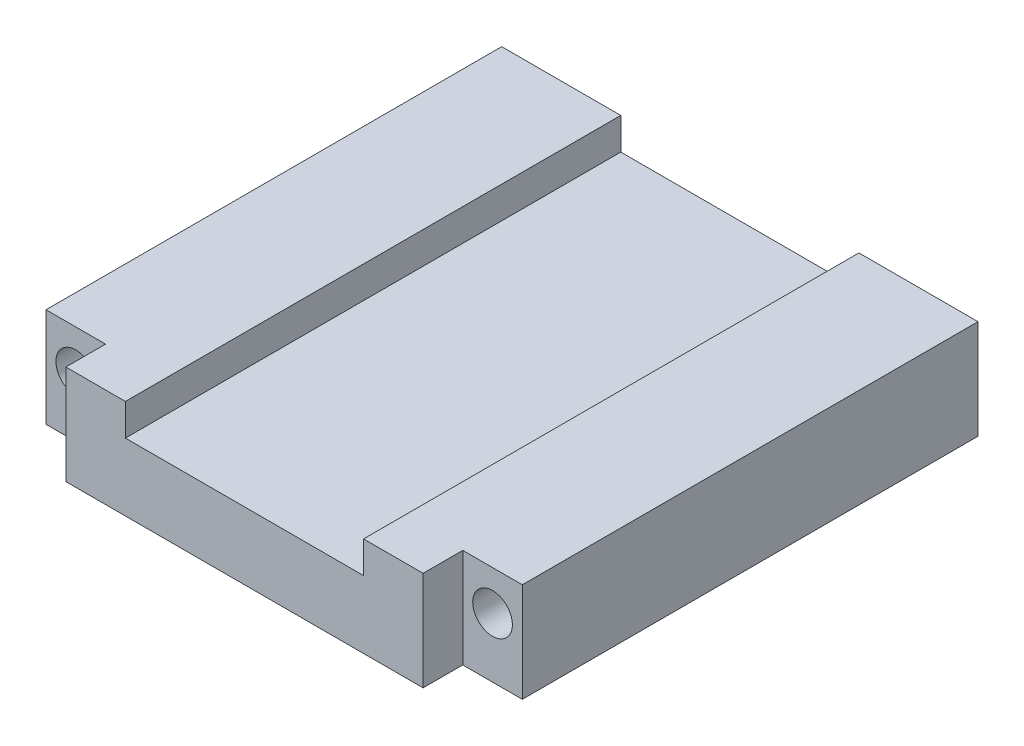
SolidWorks part; units mm, degrees
material "6063-O"
ref_plane "Front" through (0, 0, 0) normal (0, 0, 1) x (1, 0, 0)
ref_plane "Top" through (0, 0, 0) normal (0, 1, 0) x (1, 0, 0)
ref_plane "Right" through (0, 0, 0) normal (1, 0, 0) x (0, 0, -1)
sketch "Sketch1" plane through (0, 0, 0) normal (0, 0, 1) x (1, 0, 0)
  line L1 (19.05, -3.9687) -> (-19.05, -3.9688)
  line L2 (19.05, -3.9687) -> (19.05, 3.9688)
  line L3 (19.05, 3.9688) -> (-19.05, 3.9687)
  line L4 (-19.05, -3.9688) -> (-19.05, 3.9687)
  line L5 (19.05, -3.9687) -> (-19.05, 3.9687) construction
  line L6 (19.05, 3.9688) -> (-19.05, -3.9688) construction
  point P0 (0, 0)
  dimension "D1" = 7.9375
  dimension "D2" = 38.1
extrude "Boss-Extrude1" add sketch "Sketch1" along normal blind 39.624
sketch "Sketch2" plane through (0, 0, 39.624) normal (0, 0, 1) x (1, 0, 0)
  line L0 (9.525, 3.9688) -> (9.525, 1.4288)
  line L1 (19.05, 3.9688) -> (-19.05, 3.9687) construction
  line L2 (9.525, 1.4288) -> (-9.525, 1.4288)
  line L3 (-9.525, 1.4288) -> (-9.525, 3.9688)
  line L4 (-9.525, 3.9688) -> (9.525, 3.9688)
  line L5 (0, 0) -> (0, 21.8907) construction
  point P9 (0, 3.9688)
  dimension "D1" = 19.05
  dimension "D2" = 2.54
extrude "Cut-Extrude1" cut sketch "Sketch2" against normal through all
sketch "Sketch3" plane through (0, 0, 0) normal (0, 0, -1) x (-1, 0, 0)
  line L0 (-16.6687, 0.7938) -> (16.6687, 0.7938) construction
  line L3 (-19.05, 3.9688) -> (-9.525, 3.9688) construction
  line L4 (0, 0) -> (0, 0.7938) construction
  circle A0 centre (-16.6687, 0.7938) radius 1.5875
  circle A2 centre (16.6687, 0.7938) radius 1.5875
  dimension "D3" = 3.175
  dimension "D2" = 33.3375
  dimension "D1" = 3.175
hole_wizard "1/8 (0.125) Clearance Dowel Hole1" positions "Sketch7" profile "Sketch8" hole size "1/8" standard "ANSI Inch" end condition through all
sketch "Sketch7" plane through (0, 0, 0) normal (0, 0, -1) x (-1, 0, 0)
  point P0 (-16.6687, 0.7938)
  point P3 (16.6687, 0.7938)
sketch "Sketch8" plane through (16.6687, 0.7938, 0) normal (1, 0, 0) x (0, 1, 0)
  line L0 (0, 0) -> (0, 39.624)
  line L1 (0, 39.624) -> (1.5875, 39.624)
  line L2 (1.5875, 39.624) -> (1.5875, 0)
  line L5 (1.5875, 0) -> (0, 0)
  line L11 (0, -6.35) -> (0, 107.95) construction
  dimension "Thru Hole Dia." = 3.175
  dimension "Thru Hole Depth" = 39.624
sketch "Sketch6" plane through (0, 0, 39.624) normal (0, 0, 1) x (1, 0, 0)
  line L0 (-19.05, -3.9688) -> (19.05, -3.9687) construction
  line L1 (-19.05, 3.9687) -> (-14.2875, 3.9687)
  line L2 (-19.05, 3.9687) -> (-19.05, -3.9688)
  line L3 (-19.05, -3.9688) -> (-14.2875, -3.9688)
  line L4 (-14.2875, 3.9687) -> (-14.2875, -3.9688)
  line L6 (19.05, 3.9688) -> (14.2875, 3.9687)
  line L7 (19.05, 3.9688) -> (19.05, -3.9687)
  line L8 (19.05, -3.9687) -> (14.2875, -3.9688)
  line L9 (14.2875, 3.9687) -> (14.2875, -3.9688)
  dimension "D1" = 4.7625
extrude "Cut-Extrude2" cut sketch "Sketch6" against normal blind 3.175
